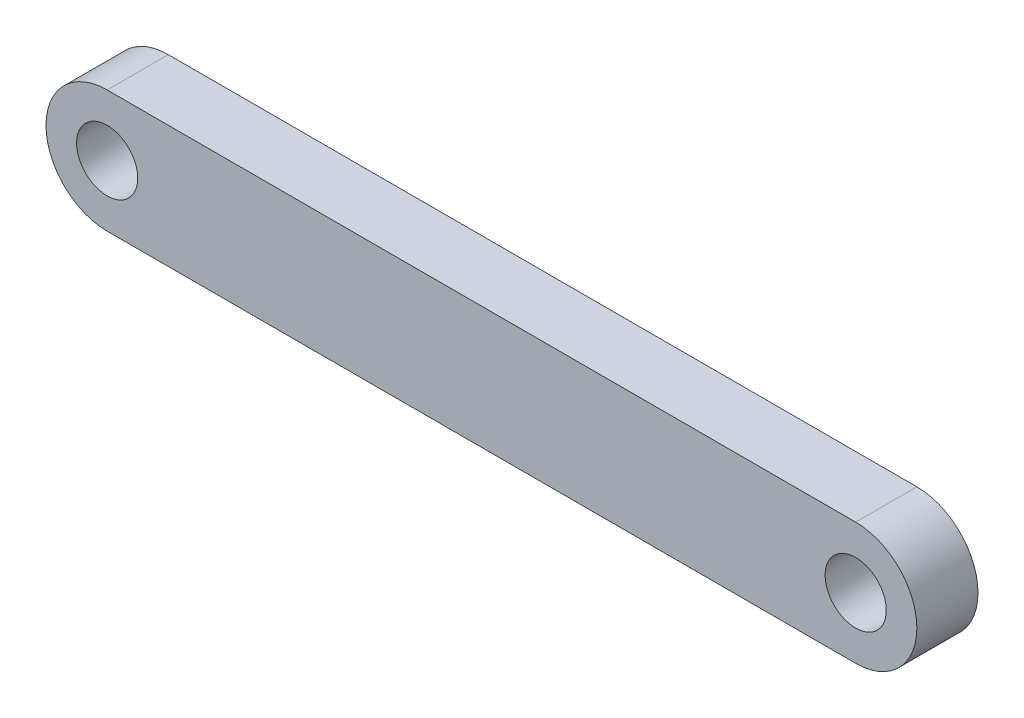
SolidWorks part; units mm, degrees
ref_plane "前基準面" through (0, 0, 0) normal (0, 0, 1) x (1, 0, 0)
ref_plane "上基準面" through (0, 0, 0) normal (0, 1, 0) x (1, 0, 0)
ref_plane "右基準面" through (0, 0, 0) normal (1, 0, 0) x (0, 0, -1)
sketch "草圖1" plane through (0, 0, 0) normal (0, 0, 1) x (1, 0, 0)
  line L0 (-12.24, 2.0006) -> (12.24, 2.0006)
  line L1 (-12.24, -1.9994) -> (12.24, -1.9994)
  arc A0 (-12.24, 2.0006) -> (-12.24, -1.9994) centre (-12.24, 0.0006) ccw
  arc A1 (12.24, -1.9994) -> (12.24, 2.0006) centre (12.24, 0.0006) ccw
  circle A2 centre (-12.24, 0.0006) radius 1
  circle A3 centre (12.24, 0.0006) radius 1
  dimension "D1" = 24.48
  dimension "D2" = 2
  dimension "D3" = 2
  dimension "D4" = 2
  dimension "D5" = 12.24
extrude "填料-伸長1" add sketch "草圖1" along normal blind 2
